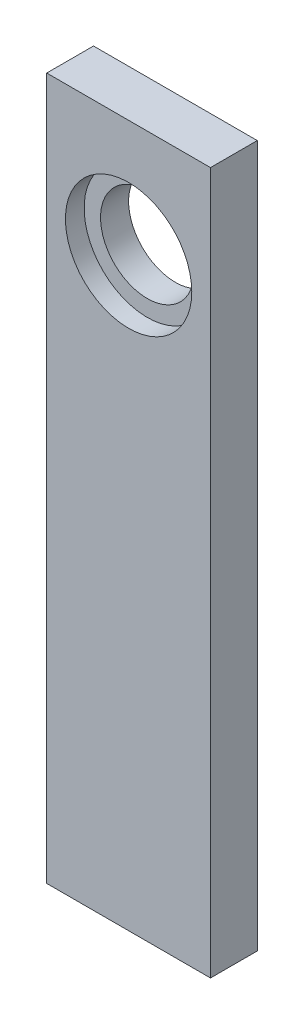
SolidWorks part; units mm, degrees
ref_plane "Front Plane" through (0, 0, 0) normal (0, 0, 1) x (1, 0, 0)
ref_plane "Top Plane" through (0, 0, 0) normal (0, 1, 0) x (1, 0, 0)
ref_plane "Right Plane" through (0, 0, 0) normal (1, 0, 0) x (0, 0, -1)
sketch "Sketch1" plane through (0, 0, 0) normal (0, 0, 1) x (1, 0, 0)
  line L0 (-17.5, 25) -> (-17.5, 125)
  line L1 (-17.5, -25) -> (17.5, -25)
  line L2 (-17.5, -25) -> (-17.5, 25)
  line L5 (-17.5, -25) -> (0, 0) construction
  line L6 (0, 0) -> (17.5, -25) construction
  line L7 (-17.5, 125) -> (17.5, 125)
  line L9 (17.5, 125) -> (17.5, -25)
  point P0 (0, 0)
  dimension "D1" = 150
  dimension "D2" = 35
extrude "Boss-Extrude1" add sketch "Sketch1" along normal blind 10
sketch "Sketch4" plane through (0, 0, 10) normal (0, 0, 1) x (1, 0, 0)
  line L0 (0, -25) -> (0, 100) construction
  line L2 (-17.5, -25) -> (17.5, -25) construction
  circle A1 centre (0, 100) radius 13.5
  dimension "D1" = 125
  dimension "D2" = 27
extrude "Cut-Extrude1" cut sketch "Sketch4" against normal blind 4
sketch "Sketch5" plane through (0, 0, 6) normal (0, 0, 1) x (1, 0, 0)
  circle A1 centre (0, 100) radius 10
  dimension "D1" = 20
extrude "Cut-Extrude2" cut sketch "Sketch5" against normal through all
